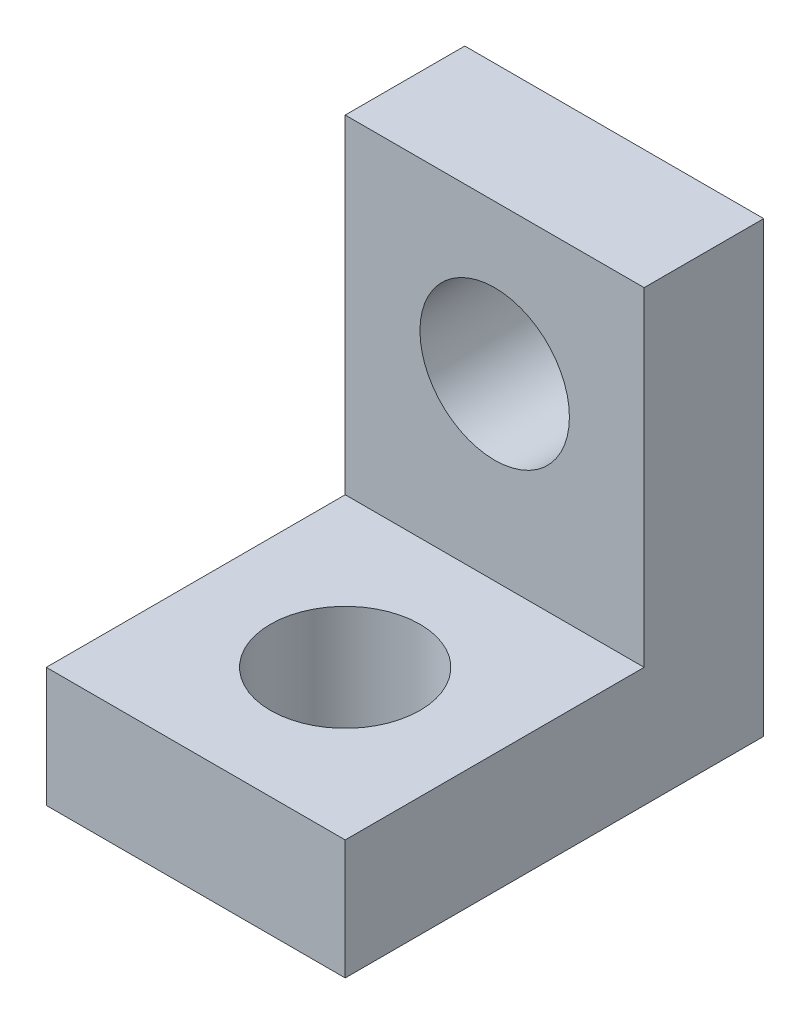
SolidWorks part; units mm, degrees
ref_plane "Front Plane" through (0, 0, 0) normal (0, 0, 1) x (1, 0, 0)
ref_plane "Top Plane" through (0, 0, 0) normal (0, 1, 0) x (1, 0, 0)
ref_plane "Right Plane" through (0, 0, 0) normal (1, 0, 0) x (0, 0, -1)
sketch "Sketch1" plane through (0, 0, 0) normal (0, 0, 1) x (1, 0, 0)
  line L1 (-5, -7.5) -> (5, -7.5)
  line L2 (-5, -7.5) -> (-5, 7.5)
  line L3 (-5, 7.5) -> (5, 7.5)
  line L4 (5, -7.5) -> (5, 7.5)
  line L5 (-5, -7.5) -> (5, 7.5) construction
  line L6 (-5, 7.5) -> (5, -7.5) construction
  circle A0 centre (0, 2.5) radius 2.5
  point P0 (0, 0)
  dimension "D3" = 5
  dimension "D1" = 15
  dimension "D2" = 10
  dimension "D4" = 5
extrude "Boss-Extrude1" add sketch "Sketch1" along normal blind 4
sketch "Sketch2" plane through (0, 0, 4) normal (0, 0, 1) x (1, 0, 0)
  line L0 (5, -7.5) -> (5, 7.5) construction
  line L1 (-5, -7.5) -> (5, -7.5)
  line L2 (-5, -7.5) -> (-5, -3.5)
  line L3 (-5, -3.5) -> (5, -3.5)
  line L4 (5, -7.5) -> (5, -3.5)
  dimension "D1" = 4
extrude "Boss-Extrude2" add sketch "Sketch2" along normal blind 10
sketch "Sketch3" plane through (0, -3.5, 0) normal (0, 1, 0) x (1, 0, 0)
  line L0 (5, -14) -> (-5, -14) construction
  circle A0 centre (0, -9) radius 2.5
  dimension "D1" = 5
  dimension "D2" = 5
extrude "Cut-Extrude1" cut sketch "Sketch3" against normal blind 10
